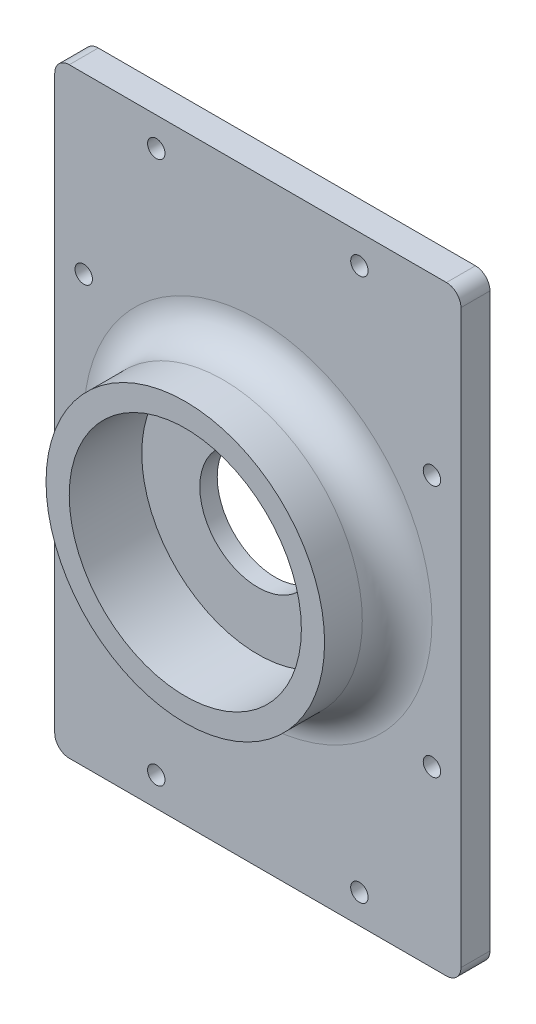
SolidWorks part; units mm, degrees
material "ABS"
ref_plane "Front Plane" through (0, 0, 0) normal (0, 0, 1) x (1, 0, 0)
ref_plane "Top Plane" through (0, 0, 0) normal (0, 1, 0) x (1, 0, 0)
ref_plane "Right Plane" through (0, 0, 0) normal (1, 0, 0) x (0, 0, -1)
sketch "Sketch1" plane through (0, 0, 0) normal (0, 0, 1) x (1, 0, 0)
  line L0 (-70, 103.5) -> (-70, -103.5)
  line L5 (-52.0206, 54.8008) -> (52.0206, -54.8008) construction
  line L6 (-52.0206, -54.8008) -> (52.0206, 54.8008) construction
  line L7 (-70, -103.5) -> (70, -103.5)
  line L8 (-70, 103.5) -> (70, 103.5)
  line L9 (70, -103.5) -> (70, 103.5)
  circle A0 centre (-35, 93.5) radius 3
  circle A1 centre (35, 93.5) radius 3
  circle A2 centre (35, -93.5) radius 3
  circle A3 centre (-35, -93.5) radius 3
  circle A4 centre (-60, -43.5) radius 3
  circle A5 centre (-60, 43.5) radius 3
  circle A6 centre (60, 43.5) radius 3
  circle A7 centre (60, -43.5) radius 3
  point P0 (0, 0)
  point P6 (-70, 0)
  dimension "D1" = 140
extrude "Boss-Extrude1" add sketch "Sketch1" along normal blind 10
sketch "Sketch2" plane through (0, 0, 10) normal (0, 0, 1) x (1, 0, 0)
  circle A0 centre (0, 0) radius 48
  circle A1 centre (0, 0) radius 40
  dimension "D1" = 80
  dimension "D2" = 8
extrude "Boss-Extrude2" add sketch "Sketch2" along normal blind 25 from surface at 0 starting at face at (0, 0, 10)
sketch "Sketch3" plane through (0, 0, 10) normal (0, 0, 1) x (1, 0, 0)
  circle A0 centre (0, 0) radius 20
  dimension "D1" = 40
extrude "Cut-Extrude1" cut sketch "Sketch3" against normal blind 25 from surface at 0 starting at face at (-40, 0, 10)
fillet "Fillet1" radius 5 4 edges at (70, -103.5, 5) (-70, -103.5, 5) (70, 103.5, 5) (-70, 103.5, 5)
sketch "Sketch4" plane through (0, 0, 0) normal (0, 0, -1) x (-1, 0, 0)
  circle A0 centre (0, 0) radius 30
  dimension "D1" = 60
extrude "Cut-Extrude2" cut sketch "Sketch4" against normal blind 4
fillet "Fillet2" radius 12 1 edges at (-48, 0, 10)
